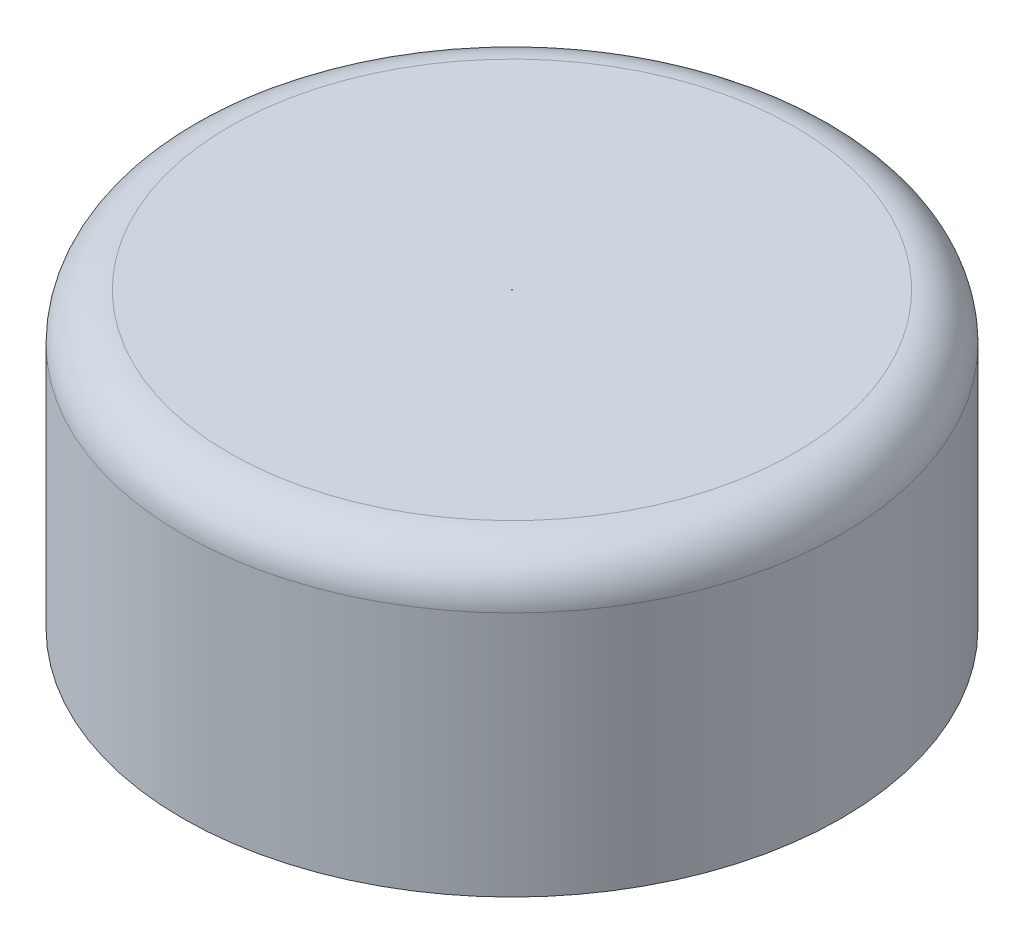
SolidWorks part; units mm, degrees
ref_plane "Front Plane" through (0, 0, 0) normal (0, 0, 1) x (1, 0, 0)
ref_plane "Top Plane" through (0, 0, 0) normal (0, 1, 0) x (1, 0, 0)
ref_plane "Right Plane" through (0, 0, 0) normal (1, 0, 0) x (0, 0, -1)
sketch "Sketch1" plane through (0, 0, 0) normal (0, 1, 0) x (1, 0, 0)
  circle A0 centre (0, 0) radius 14.2875
  dimension "D1" = 28.575
extrude "Boss-Extrude1" add sketch "Sketch1" along normal blind 12.7
fillet "Fillet1" radius 2.032 1 edges at (0, 12.7, 14.2875)
shell "Shell1" thickness 2.54
sketch "Sketch2" plane through (0, 12.7, 0) normal (0, 1, 0) x (1, 0, 0)
  circle A0 centre (0, 0) radius 0.0127
  dimension "D1" = 0.0254
extrude "Cut-Extrude1" cut sketch "Sketch2" against normal up to next
